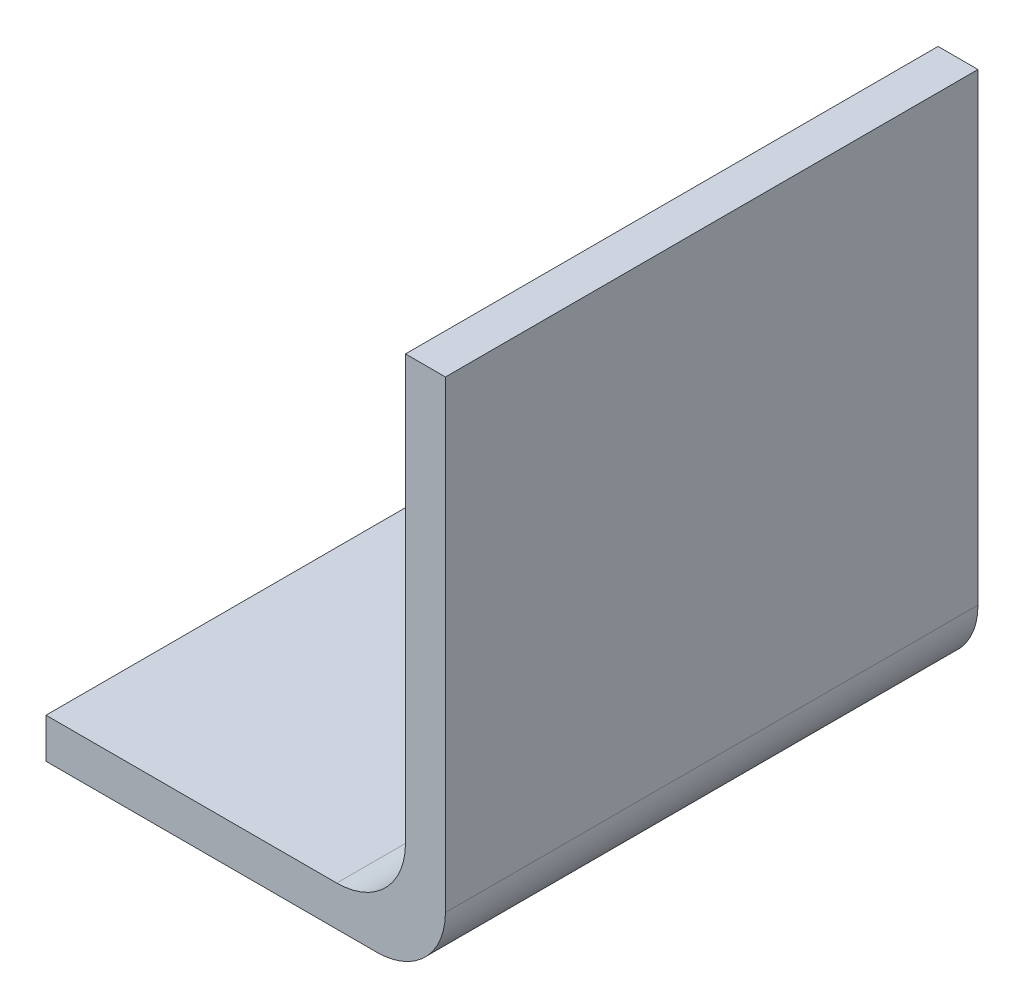
SolidWorks part; units mm, degrees
ref_plane "Front Plane" through (0, 0, 0) normal (0, 0, 1) x (1, 0, 0)
ref_plane "Top Plane" through (0, 0, 0) normal (0, 1, 0) x (1, 0, 0)
ref_plane "Right Plane" through (0, 0, 0) normal (1, 0, 0) x (0, 0, -1)
sketch "Sketch2" plane through (0, 0, 0) normal (0, 0, 1) x (1, 0, 0)
  line L0 (0, 0) -> (24.8369, 0)
  line L1 (30, 5.1631) -> (30, 40)
  line L2 (30, 40) -> (27, 40)
  line L3 (27, 40) -> (27, 8.1631)
  line L4 (21.8369, 3) -> (0, 3)
  line L5 (0, 3) -> (0, 0)
  arc A0 (27, 8.1631) -> (21.8369, 3) centre (21.8369, 8.1631) cw
  arc A1 (24.8369, 0) -> (30, 5.1631) centre (24.8369, 5.1631) ccw
  point P11 (30, 0)
  dimension "D5" = 5.1631
  dimension "D1" = 40
  dimension "D2" = 30
  dimension "D3" = 3
  dimension "D4" = 3
extrude "Boss-Extrude1" add sketch "Sketch2" along normal blind 40
sketch "Sketch3" plane through (0, 3, 0) normal (0, 1, 0) x (1, 0, 0)
  circle A0 centre (14.7097, -20) radius 5
extrude "Cut-Extrude1" cut sketch "Sketch3" against normal blind 40
